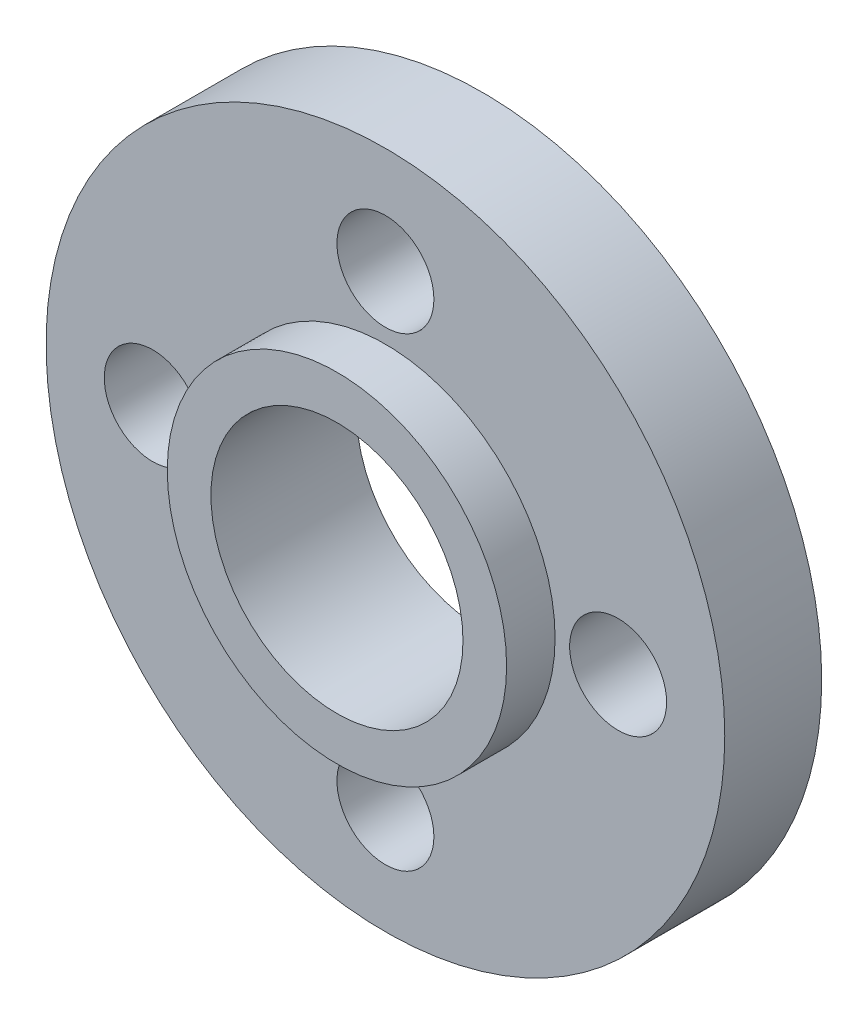
SolidWorks part; units mm, degrees
ref_plane "Спереди" through (0, 0, 0) normal (0, 0, 1) x (1, 0, 0)
ref_plane "Сверху" through (0, 0, 0) normal (0, 1, 0) x (1, 0, 0)
ref_plane "Справа" through (0, 0, 0) normal (1, 0, 0) x (0, 0, -1)
sketch "Эскиз2" plane through (0, 0, 0) normal (0, 0, 1) x (1, 0, 0)
  line L0 (0, 0) -> (-7, 0) construction
  circle A0 centre (0, 0) radius 2.6
  circle A1 centre (0, 0) radius 7
  circle A2 centre (-4.8, 0) radius 1
  circle A3 centre (0, 4.8) radius 1
  circle A4 centre (4.8, 0) radius 1
  circle A5 centre (0, -4.8) radius 1
  point P16 (0, 0)
  dimension "D1" = 14
  dimension "D2" = 5.2
  dimension "D3" = 2
  dimension "D4" = 4.8
  dimension "D5" = 4
extrude "Бобышка-Вытянуть1" add sketch "Эскиз2" along normal blind 2
sketch "Эскиз3" plane through (0, 0, 2) normal (0, 0, 1) x (1, 0, 0)
  circle A0 centre (0, 0) radius 2.6
  circle A1 centre (0, 0) radius 3.5
  dimension "D1" = 7
  dimension "D2" = 5.2
extrude "Бобышка-Вытянуть2" add sketch "Эскиз3" along normal blind 1
